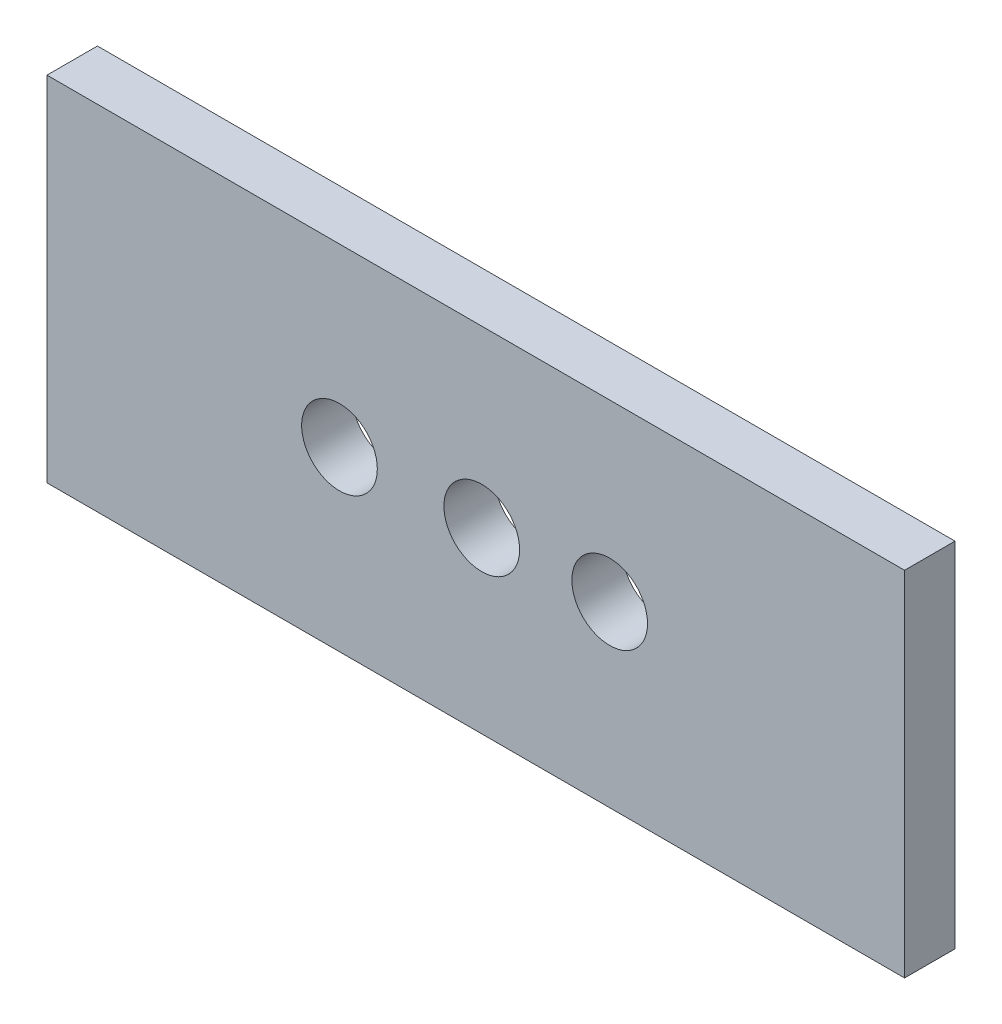
SolidWorks part; units mm, degrees
material "PETG"
ref_plane "Front Plane" through (0, 0, 0) normal (0, 0, 1) x (1, 0, 0)
ref_plane "Top Plane" through (0, 0, 0) normal (0, 1, 0) x (1, 0, 0)
ref_plane "Right Plane" through (0, 0, 0) normal (1, 0, 0) x (0, 0, -1)
sketch "Sketch1" plane through (0.0993, 0, 0) normal (0, 0, 1) x (1, 0, 0)
  line L1 (-37.1551, 61.1735) -> (-3.1551, 61.1735)
  line L2 (-37.1551, 61.1735) -> (-37.1551, 47.1735)
  line L3 (-37.1551, 47.1735) -> (-3.1551, 47.1735)
  line L4 (-3.1551, 61.1735) -> (-3.1551, 47.1735)
  line L5 (-37.1551, 61.1735) -> (-3.1551, 47.1735) construction
  line L6 (-37.1551, 47.1735) -> (-3.1551, 61.1735) construction
  point P0 (-20.1551, 54.1735)
extrude "Boss-Extrude1" add sketch "Sketch1" along normal blind 2 contours L1 L4 L3 L2
sketch "Sketch3" plane through (0.0993, 0, 2) normal (0, 0, 1) x (1, 0, 0)
  circle A0 centre (-25.5587, 54.1972) radius 1.5
sketch "Sketch4" plane through (0.0993, 0, 2) normal (0, 0, 1) x (1, 0, 0)
  circle A0 centre (-19.9181, 54.2446) radius 1.5
  circle A1 centre (-14.8463, 54.2446) radius 1.5
extrude "Cut-Extrude1" cut sketch "Sketch3" against normal blind 2
extrude "Cut-Extrude2" cut sketch "Sketch4" against normal blind 2
